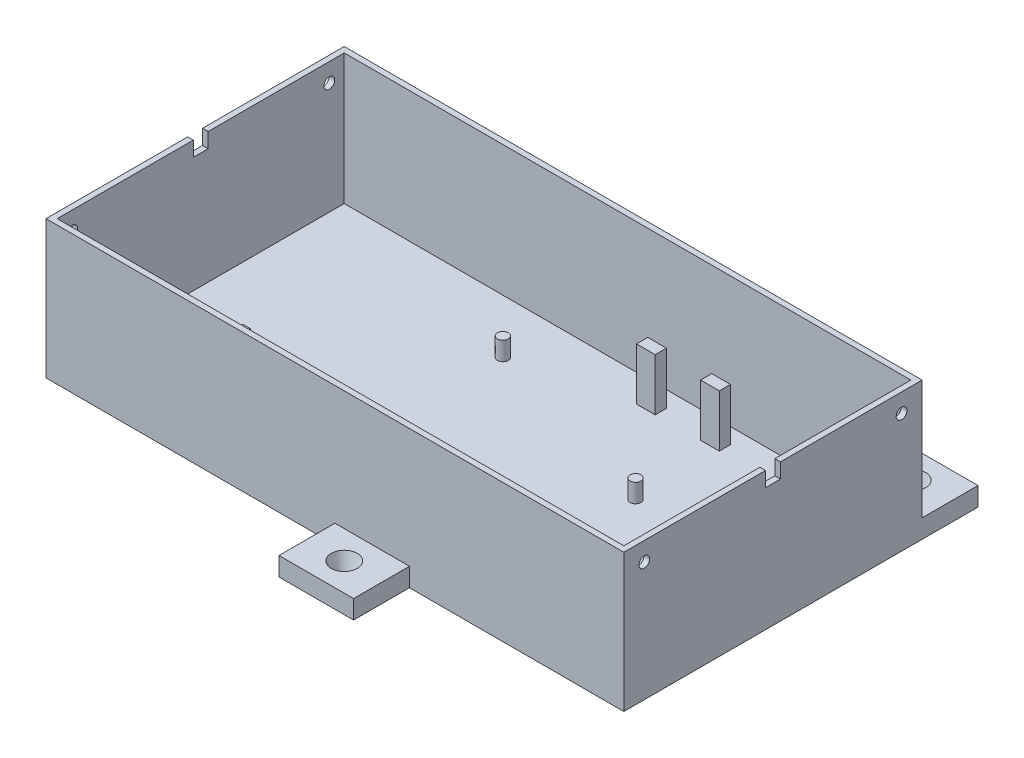
SolidWorks part; units mm, degrees
ref_plane "Front Plane" through (0, 0, 0) normal (0, 0, 1) x (1, 0, 0)
ref_plane "Top Plane" through (0, 0, 0) normal (0, 1, 0) x (1, 0, 0)
ref_plane "Right Plane" through (0, 0, 0) normal (1, 0, 0) x (0, 0, -1)
sketch "Sketch1" plane through (0, 0, 0) normal (0, 1, 0) x (1, 0, 0)
  line L1 (77.5, -40) -> (-77.5, -40)
  line L2 (77.5, -40) -> (77.5, 40)
  line L3 (77.5, 40) -> (-77.5, 40)
  line L4 (-77.5, -40) -> (-77.5, 40)
  line L5 (77.5, -40) -> (-77.5, 40) construction
  line L6 (77.5, 40) -> (-77.5, -40) construction
  point P0 (0, 0)
extrude "Boss-Extrude1" add sketch "Sketch1" along normal blind 2
ref_plane "Plane1" through (0, 2, 0) normal (0, 1, 0) x (1, 0, 0)
sketch "Sketch3" plane through (0, 2, 0) normal (0, 1, 0) x (1, 0, 0)
  circle A0 centre (-20.3, -24.15) radius 1.45
  circle A1 centre (-19, 24.05) radius 1.45
  circle A2 centre (31.8, 8.85) radius 1.45
  circle A3 centre (31.8, -19.05) radius 1.45
extrude "Boss-Extrude2" add sketch "Sketch3" along normal blind 5
sketch "Sketch4" plane through (0, 2, 0) normal (0, 1, 0) x (1, 0, 0)
  line L2 (31.8, 31.3) -> (26.8, 31.3)
  line L3 (31.8, 31.3) -> (31.8, 34.3)
  line L4 (31.8, 34.3) -> (26.8, 34.3)
  line L5 (26.8, 31.3) -> (26.8, 34.3)
extrude "Boss-Extrude3" add sketch "Sketch4" along normal blind 14
sketch "Sketch5" plane through (0, 2, 0) normal (0, 1, 0) x (1, 0, 0)
  line L3 (14.7874, 34.1181) -> (9.7874, 34.1181)
  line L4 (14.7874, 34.1181) -> (14.7874, 31.1181)
  line L5 (14.7874, 31.1181) -> (9.7874, 31.1181)
  line L6 (9.7874, 34.1181) -> (9.7874, 31.1181)
extrude "Boss-Extrude4" add sketch "Sketch5" along normal blind 14
sketch "Sketch6" plane through (0, 2, 0) normal (0, 1, 0) x (1, 0, 0)
  line L2 (36.8, -32) -> (26.8, -32)
  line L3 (36.8, -32) -> (36.8, -29)
  line L4 (36.8, -29) -> (26.8, -29)
  line L5 (26.8, -32) -> (26.8, -29)
  line L6 (36.8, -32) -> (26.8, -29) construction
  line L7 (36.8, -29) -> (26.8, -32) construction
extrude "Boss-Extrude5" add sketch "Sketch6" along normal blind 14
sketch "Sketch7" plane through (0, 2, 0) normal (0, 1, 0) x (1, 0, 0)
  line L2 (-38.5558, -24.15) -> (-40.5558, -24.15)
  line L3 (-38.5558, -24.15) -> (-38.5558, -27.15)
  line L4 (-38.5558, -27.15) -> (-40.5558, -27.15)
  line L5 (-40.5558, -24.15) -> (-40.5558, -27.15)
extrude "Boss-Extrude6" add sketch "Sketch7" along normal blind 21
sketch "Sketch8" plane through (0, 2, 0) normal (0, 1, 0) x (1, 0, 0)
  line L0 (-77.5, 40) -> (-77.5, -40) construction
  line L1 (77.5, 40) -> (-77.5, 40)
  line L2 (77.5, 40) -> (77.5, 38.5)
  line L3 (77.5, 38.5) -> (-77.5, 38.5)
  line L4 (-77.5, 40) -> (-77.5, 38.5)
extrude "Boss-Extrude7" add sketch "Sketch8" along normal blind 35
sketch "Sketch9" plane through (0, 2, 0) normal (0, 1, 0) x (1, 0, 0)
  line L0 (77.5, -40) -> (77.5, 38.5) construction
  line L1 (-77.5, -40) -> (77.5, -40)
  line L2 (-77.5, -40) -> (-77.5, -38.5)
  line L3 (-77.5, -38.5) -> (77.5, -38.5)
  line L4 (77.5, -40) -> (77.5, -38.5)
extrude "Boss-Extrude8" add sketch "Sketch9" along normal blind 35
sketch "Sketch10" plane through (0, 2, 0) normal (0, 1, 0) x (1, 0, 0)
  line L0 (-77.5, 38.5) -> (77.5, 38.5) construction
  line L1 (77.5, -38.5) -> (76, -38.5)
  line L2 (77.5, -38.5) -> (77.5, 38.5)
  line L3 (77.5, 38.5) -> (76, 38.5)
  line L4 (76, -38.5) -> (76, 38.5)
extrude "Boss-Extrude9" add sketch "Sketch10" along normal blind 35
sketch "Sketch11" plane through (0, 2, 0) normal (0, 1, 0) x (1, 0, 0)
  line L0 (76, -38.5) -> (-77.5, -38.5) construction
  line L1 (-77.5, -38.5) -> (-76, -38.5)
  line L2 (-77.5, -38.5) -> (-77.5, 38.5)
  line L3 (-77.5, 38.5) -> (-76, 38.5)
  line L4 (-76, -38.5) -> (-76, 38.5)
  line L5 (-77.5, 38.5) -> (-77.5, -38.5) construction
  line L6 (-77.5, 38.5) -> (76, 38.5) construction
extrude "Boss-Extrude10" add sketch "Sketch11" along normal blind 35
ref_plane "Plane2" through (-77.5, 0, 0) normal (-1, 0, 0) x (0, 0, 1)
sketch "Sketch12" plane through (-77.5, 0, 0) normal (-1, 0, 0) x (0, 0, 1)
  line L0 (-40, 37) -> (40, 37) construction
  line L2 (-2, 41) -> (2, 41)
  line L3 (-2, 41) -> (-2, 33)
  line L4 (-2, 33) -> (2, 33)
  line L5 (2, 41) -> (2, 33)
  line L6 (-2, 41) -> (2, 33) construction
  line L7 (-2, 33) -> (2, 41) construction
  point P0 (0, 37)
extrude "Cut-Extrude1" cut sketch "Sketch12" against normal blind 5
ref_plane "Plane3" through (77.5, 0, 0) normal (1, 0, 0) x (0, 0, -1)
sketch "Sketch13" plane through (77.5, 0, 0) normal (1, 0, 0) x (0, 0, -1)
  line L0 (-40, 37) -> (40, 37) construction
  line L1 (2, 41) -> (-2, 41)
  line L2 (2, 41) -> (2, 33)
  line L3 (2, 33) -> (-2, 33)
  line L4 (-2, 41) -> (-2, 33)
  line L5 (2, 41) -> (-2, 33) construction
  line L6 (2, 33) -> (-2, 41) construction
  point P0 (0, 37)
extrude "Cut-Extrude2" cut sketch "Sketch13" against normal blind 5
ref_plane "Plane4" through (0, 0, -40) normal (0, 0, -1) x (-1, 0, 0)
sketch "Sketch14" plane through (0, 0, -40) normal (0, 0, -1) x (-1, 0, 0)
  line L2 (-77.5, 0) -> (-57.5, 0)
  line L3 (-77.5, 0) -> (-77.5, 5)
  line L4 (-77.5, 5) -> (-57.5, 5)
  line L5 (-57.5, 0) -> (-57.5, 5)
  line L6 (77.5, 0) -> (57.5, 0)
  line L7 (77.5, 0) -> (77.5, 5)
  line L8 (77.5, 5) -> (57.5, 5)
  line L9 (57.5, 0) -> (57.5, 5)
extrude "Boss-Extrude11" add sketch "Sketch14" along normal blind 15
ref_plane "Plane5" through (0, 0, 40) normal (0, 0, 1) x (1, 0, 0)
sketch "Sketch15" plane through (0, 0, 40) normal (0, 0, 1) x (1, 0, 0)
  line L1 (0, 0) -> (20, 0)
  line L2 (0, 0) -> (0, 5)
  line L3 (0, 5) -> (20, 5)
  line L4 (20, 0) -> (20, 5)
extrude "Boss-Extrude12" add sketch "Sketch15" along normal blind 15
ref_plane "Plane6" through (0, 5, 0) normal (0, 1, 0) x (1, 0, 0)
sketch "Sketch16" plane through (0, 5, 0) normal (0, 1, 0) x (1, 0, 0)
  circle A0 centre (67.5, 47.5) radius 1.95
extrude "Cut-Extrude3" cut sketch "Sketch16" against normal blind 5
sketch "Sketch17" plane through (0, 5, 0) normal (0, 1, 0) x (1, 0, 0)
  circle A0 centre (67.5, 47.5) radius 3.5
extrude "Cut-Extrude4" cut sketch "Sketch17" against normal blind 10 draft 18
ref_plane "Plane7" through (0, 5, 0) normal (0, 1, 0) x (1, 0, 0)
sketch "Sketch18" plane through (0, 5, 0) normal (0, 1, 0) x (1, 0, 0)
  circle A0 centre (-67.5, 47.5) radius 1.95
extrude "Cut-Extrude5" cut sketch "Sketch18" against normal blind 10
sketch "Sketch19" plane through (0, 5, 0) normal (0, 1, 0) x (1, 0, 0)
  circle A0 centre (-67.5, 47.5) radius 3.5
extrude "Cut-Extrude6" cut sketch "Sketch19" against normal blind 10 draft 18
ref_plane "Plane8" through (0, 5, 0) normal (0, 1, 0) x (1, 0, 0)
sketch "Sketch20" plane through (0, 5, 0) normal (0, 1, 0) x (1, 0, 0)
  circle A0 centre (10, -47.5) radius 1.95
extrude "Cut-Extrude7" cut sketch "Sketch20" against normal blind 10
sketch "Sketch21" plane through (0, 5, 0) normal (0, 1, 0) x (1, 0, 0)
  circle A0 centre (10, -47.5) radius 3.5
extrude "Cut-Extrude8" cut sketch "Sketch21" against normal blind 10 draft 18
ref_plane "Plane9" through (77.5, 0, 0) normal (1, 0, 0) x (0, 0, -1)
sketch "Sketch22" plane through (77.5, 0, 0) normal (1, 0, 0) x (0, 0, -1)
  circle A0 centre (-34.5, 32) radius 1.45
extrude "Cut-Extrude9" cut sketch "Sketch22" against normal blind 200
sketch "Sketch23" plane through (77.5, 0, 0) normal (1, 0, 0) x (0, 0, -1)
  circle A0 centre (34.5, 32) radius 1.45
extrude "Cut-Extrude10" cut sketch "Sketch23" against normal blind 200
